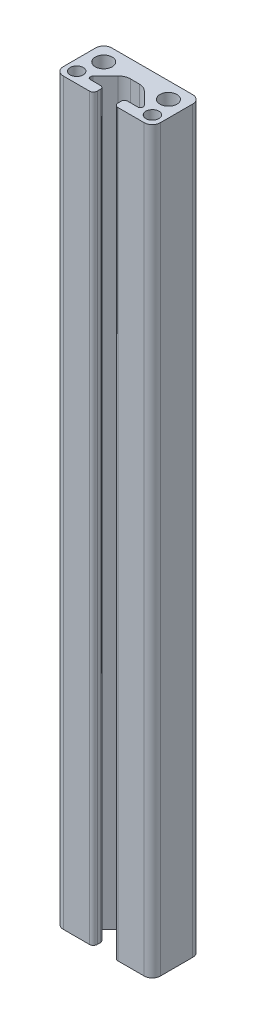
SolidWorks part; units mm, degrees
ref_plane "Front" through (0, 0, 0) normal (0, 0, 1) x (1, 0, 0)
ref_plane "Top" through (0, 0, 0) normal (0, 1, 0) x (1, 0, 0)
ref_plane "Right" through (0, 0, 0) normal (1, 0, 0) x (0, 0, -1)
sketch "Sketch1" plane through (0, 0, 0) normal (0, 0, 1) x (1, 0, 0)
  line L0 (0, 145) -> (0, -145)
  dimension "D1" = 290
other "15 1575 PROFILE(1)"
ref_plane "Plane1" through (0, 145, 0) normal (0, -1, 0) x (1, 0, 0)
sketch "Sketch16" plane through (0, 145, 0) normal (0, -1, 0) x (1, 0, 0)
  line L1 (19.05, -9.525) -> (-19.05, -9.525) construction
  line L2 (19.05, -9.525) -> (19.05, 9.525) construction
  line L3 (19.05, 9.525) -> (-19.05, 9.525) construction
  line L4 (-19.05, -9.525) -> (-19.05, 9.525) construction
  line L5 (19.05, -9.525) -> (-19.05, 9.525) construction
  line L6 (19.05, 9.525) -> (-19.05, -9.525) construction
  line L28 (-9.398, 5.461) -> (-5.334, 5.461)
  line L29 (-4.064, 6.731) -> (-4.064, 8.001)
  line L30 (-5.588, 9.525) -> (-15.875, 9.525)
  line L31 (-19.05, 6.35) -> (-19.05, -6.35)
  line L32 (-15.875, -9.525) -> (15.875, -9.525)
  line L33 (19.05, -6.35) -> (19.05, 6.35)
  line L34 (15.875, 9.525) -> (5.588, 9.525)
  line L35 (4.064, 8.001) -> (4.064, 6.731)
  line L36 (5.334, 5.461) -> (9.398, 5.461)
  line L37 (10.287, 4.572) -> (10.287, 4.2554)
  line L38 (10.0266, 3.6267) -> (5.1241, -1.2758)
  line L39 (1.7654, -2.667) -> (-1.7654, -2.667)
  line L40 (-5.1241, -1.2758) -> (-10.0266, 3.6267)
  line L41 (-10.287, 4.2554) -> (-10.287, 4.572)
  circle A1 centre (-12.7, -3.175) radius 3.3274
  circle A3 centre (-14.8488, 5.2764) radius 2.5527
  circle A5 centre (12.7, -3.175) radius 3.3274
  circle A7 centre (14.8488, 5.2764) radius 2.5527
  arc A28 (-9.398, 5.461) -> (-10.287, 4.572) centre (-9.398, 4.572) ccw
  arc A29 (-5.334, 5.461) -> (-4.064, 6.731) centre (-5.334, 6.731) ccw
  arc A30 (-4.064, 8.001) -> (-5.588, 9.525) centre (-5.588, 8.001) ccw
  arc A31 (-15.875, 9.525) -> (-19.05, 6.35) centre (-15.875, 6.35) ccw
  arc A32 (-19.05, -6.35) -> (-15.875, -9.525) centre (-15.875, -6.35) ccw
  arc A33 (15.875, -9.525) -> (19.05, -6.35) centre (15.875, -6.35) ccw
  arc A34 (19.05, 6.35) -> (15.875, 9.525) centre (15.875, 6.35) ccw
  arc A35 (5.588, 9.525) -> (4.064, 8.001) centre (5.588, 8.001) ccw
  arc A36 (4.064, 6.731) -> (5.334, 5.461) centre (5.334, 6.731) ccw
  arc A37 (10.287, 4.572) -> (9.398, 5.461) centre (9.398, 4.572) ccw
  arc A38 (10.0266, 3.6267) -> (10.287, 4.2554) centre (9.398, 4.2554) ccw
  arc A39 (1.7654, -2.667) -> (5.1241, -1.2758) centre (1.7654, 2.0828) ccw
  arc A40 (-5.1241, -1.2758) -> (-1.7654, -2.667) centre (-1.7654, 2.0828) ccw
  arc A41 (-10.287, 4.2554) -> (-10.0266, 3.6267) centre (-9.398, 4.2554) ccw
  point P3 (0, 0)
  point P39 (0, 9.525)
  point P56 (0, -9.525)
  point P57 (19.05, -9.525)
  point P58 (19.05, 9.525)
  point P59 (-19.05, 9.525)
  point P60 (-19.05, -9.525)
  point P61 (0, 0)
  dimension "D1" = 19.05
  dimension "D2" = 38.1
